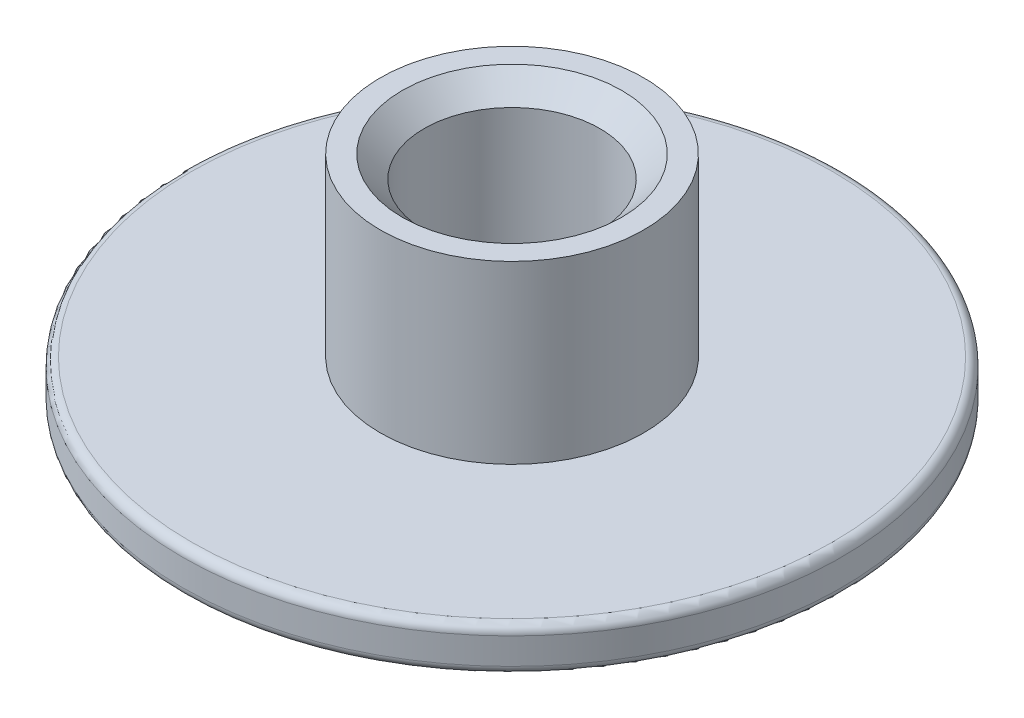
SolidWorks part; units mm, degrees
ref_plane "前视基准面" through (0, 0, 0) normal (0, 0, 1) x (1, 0, 0)
ref_plane "上视基准面" through (0, 0, 0) normal (0, 1, 0) x (1, 0, 0)
ref_plane "右视基准面" through (0, 0, 0) normal (1, 0, 0) x (0, 0, -1)
sketch "草图1" plane through (0, 0, 0) normal (0, 1, 0) x (1, 0, 0)
  circle A0 centre (0, 0) radius 7.5
  dimension "D1" = 15
extrude "凸台-拉伸1" add sketch "草图1" along normal blind 1
sketch "草图2" plane through (0, 1, 0) normal (0, 1, 0) x (1, 0, 0)
  circle A0 centre (0, 0) radius 3
  dimension "D1" = 6
extrude "凸台-拉伸2" add sketch "草图2" along normal blind 4
sketch "草图3" plane through (0, 5, 0) normal (0, 1, 0) x (1, 0, 0)
  circle A0 centre (0, 0) radius 2
  dimension "D1" = 4
extrude "切除-拉伸1" cut sketch "草图3" against normal up to next
chamfer "倒角1" distance 0.5 angle 45 2 edges at (0, 0, 2) (0, 5, 2)
fillet "圆角1" radius 0.2 2 edges at (0, 0, 7.5) (0, 1, 7.5)
